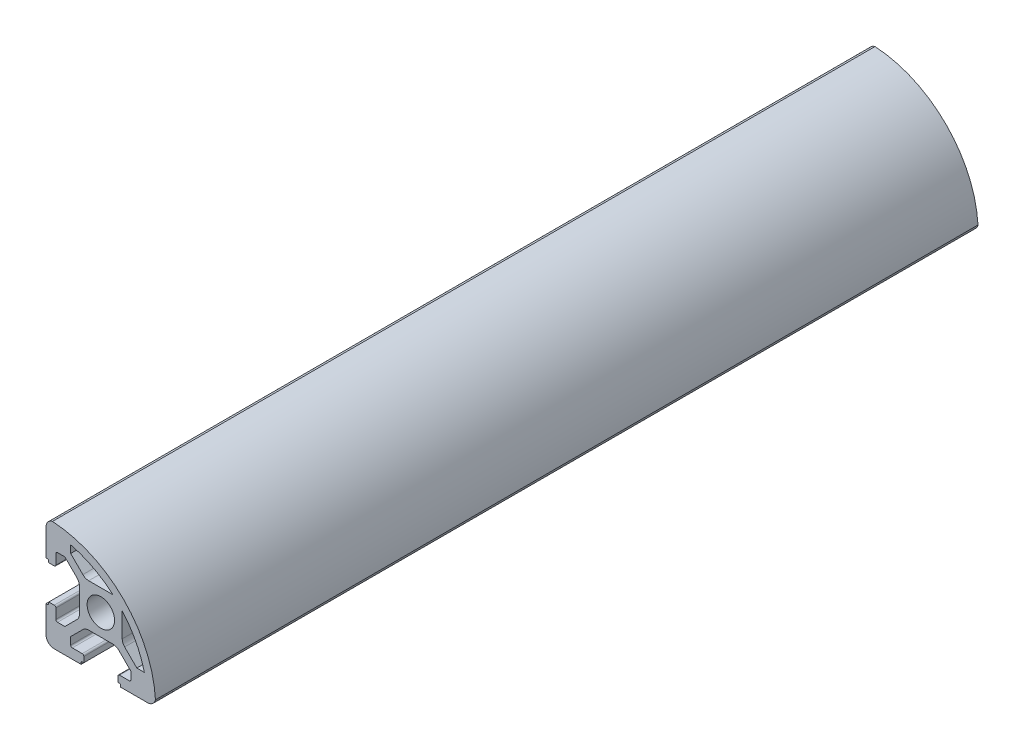
SolidWorks part; units mm, degrees
ref_plane "前视基准面" through (0, 0, 0) normal (0, 0, 1) x (1, 0, 0)
ref_plane "上视基准面" through (0, 0, 0) normal (0, 1, 0) x (1, 0, 0)
ref_plane "右视基准面" through (0, 0, 0) normal (1, 0, 0) x (0, 0, -1)
sketch "草图1" plane through (0, 0, 0) normal (0, 0, 1) x (1, 0, 0)
  line L14 (2.0848, 3.8649) -> (-2.342, 3.8649)
  line L15 (-3.4027, 4.3042) -> (-5.6233, 6.5249)
  line L16 (-5.6233, 6.5249) -> (-5.6233, 7.8649)
  line L22 (-10.1233, 8.4649) -> (-10.1233, 3.5649)
  line L23 (-10.1233, 3.5649) -> (-9.8233, 3.5649)
  line L24 (-9.6233, 3.3649) -> (-9.6233, 3.0649)
  line L25 (-9.6233, 3.0649) -> (-8.6233, 3.0649)
  line L26 (-8.3233, 3.3649) -> (-8.3233, 5.1649)
  line L27 (-8.0233, 5.4649) -> (-6.6833, 5.4649)
  line L28 (-6.6833, 5.4649) -> (-4.4627, 3.2442)
  line L29 (-4.0233, 2.1836) -> (-4.0233, -2.2538)
  line L30 (-4.4627, -3.3144) -> (-6.6833, -5.5351)
  line L31 (-6.6833, -5.5351) -> (-8.0233, -5.5351)
  line L32 (-8.3233, -5.2351) -> (-8.3233, -3.4351)
  line L33 (-8.6233, -3.1351) -> (-9.6233, -3.1351)
  line L34 (-9.6233, -3.1351) -> (-9.6233, -3.4351)
  line L35 (-9.8233, -3.6351) -> (-10.1233, -3.6351)
  line L36 (-10.1233, -3.6351) -> (-10.1233, -8.5351)
  line L37 (-8.6233, -10.0351) -> (-3.7233, -10.0351)
  line L38 (-3.7233, -10.0351) -> (-3.7233, -9.7351)
  line L39 (-3.5233, -9.5351) -> (-3.2233, -9.5351)
  line L40 (-3.2233, -9.5351) -> (-3.2233, -8.5351)
  line L41 (-3.5233, -8.2351) -> (-5.3233, -8.2351)
  line L42 (-5.6233, -7.9351) -> (-5.6233, -6.5951)
  line L43 (-5.6233, -6.5951) -> (-3.4027, -4.3744)
  line L44 (-2.342, -3.9351) -> (2.0953, -3.9351)
  line L45 (3.156, -4.3744) -> (5.3767, -6.5951)
  line L46 (5.3767, -6.5951) -> (5.3767, -7.9351)
  line L47 (5.0767, -8.2351) -> (3.2767, -8.2351)
  line L48 (2.9767, -8.5351) -> (2.9767, -9.5351)
  line L49 (2.9767, -9.5351) -> (3.2767, -9.5351)
  line L50 (3.4767, -9.7351) -> (3.4767, -10.0351)
  line L51 (3.4767, -10.0351) -> (8.3767, -10.0351)
  line L57 (7.7767, -5.5351) -> (6.4367, -5.5351)
  line L58 (6.4367, -5.5351) -> (4.216, -3.3144)
  line L59 (3.7767, -2.2538) -> (3.7767, 2.1836)
  circle A0 centre (-0.1233, -0.0351) radius 2.5
  arc A1 (7.8202, -5.5319) -> (3.7767, 2.1731) centre (-10.1233, -10.0351) ccw
  arc A2 (2.0848, 3.8649) -> (-5.6202, 7.9085) centre (-10.1233, -10.0351) ccw
  arc A9 (-3.4027, 4.3042) -> (-2.342, 3.8649) centre (-2.342, 5.3649) ccw
  arc A10 (-5.3233, 8.1649) -> (-5.6233, 7.8649) centre (-5.3233, 7.8649) ccw
  arc A13 (-8.6233, 9.9649) -> (-10.1233, 8.4649) centre (-8.6233, 8.4649) ccw
  arc A14 (-9.6233, 3.3649) -> (-9.8233, 3.5649) centre (-9.8233, 3.3649) ccw
  arc A15 (-8.6233, 3.0649) -> (-8.3233, 3.3649) centre (-8.6233, 3.3649) ccw
  arc A16 (-8.0233, 5.4649) -> (-8.3233, 5.1649) centre (-8.0233, 5.1649) ccw
  arc A17 (-4.0233, 2.1836) -> (-4.4627, 3.2442) centre (-5.5233, 2.1836) ccw
  arc A18 (-4.4627, -3.3144) -> (-4.0233, -2.2538) centre (-5.5233, -2.2538) ccw
  arc A19 (-8.3233, -5.2351) -> (-8.0233, -5.5351) centre (-8.0233, -5.2351) ccw
  arc A20 (-8.3233, -3.4351) -> (-8.6233, -3.1351) centre (-8.6233, -3.4351) ccw
  arc A21 (-9.8233, -3.6351) -> (-9.6233, -3.4351) centre (-9.8233, -3.4351) ccw
  arc A22 (-10.1233, -8.5351) -> (-8.6233, -10.0351) centre (-8.6233, -8.5351) ccw
  arc A23 (-3.5233, -9.5351) -> (-3.7233, -9.7351) centre (-3.5233, -9.7351) ccw
  arc A24 (-3.2233, -8.5351) -> (-3.5233, -8.2351) centre (-3.5233, -8.5351) ccw
  arc A25 (-5.6233, -7.9351) -> (-5.3233, -8.2351) centre (-5.3233, -7.9351) ccw
  arc A26 (-2.342, -3.9351) -> (-3.4027, -4.3744) centre (-2.342, -5.4351) ccw
  arc A27 (3.156, -4.3744) -> (2.0953, -3.9351) centre (2.0953, -5.4351) ccw
  arc A28 (5.0767, -8.2351) -> (5.3767, -7.9351) centre (5.0767, -7.9351) ccw
  arc A29 (3.2767, -8.2351) -> (2.9767, -8.5351) centre (3.2767, -8.5351) ccw
  arc A30 (3.4767, -9.7351) -> (3.2767, -9.5351) centre (3.2767, -9.7351) ccw
  arc A31 (8.3767, -10.0351) -> (9.8767, -8.5351) centre (8.3767, -8.5351) ccw
  arc A34 (7.7767, -5.5351) -> (7.8202, -5.5319) centre (7.7767, -5.2351) ccw
  arc A35 (3.7767, -2.2538) -> (4.216, -3.3144) centre (5.2767, -2.2538) ccw
  arc A37 (9.8419, -8.8562) -> (-8.9445, 9.9301) centre (-10.1233, -10.0351) ccw
extrude "凸台-拉伸1" add sketch "草图1" along normal blind 150 contours A31 A37 A13 L22 L23 A14 L24 L25 A15 L26 A16 L27 L28 A17 L29 A18 L30 L31 A19 L32 A20 L33 L34 A21 L35 L36 A22 L37 L38 A23 L39 L40 A24 L41 A25 L42 L43 A26 L44 A27 L45 L46 A28 L47 A29 L48 L49 A30 L50 L51
